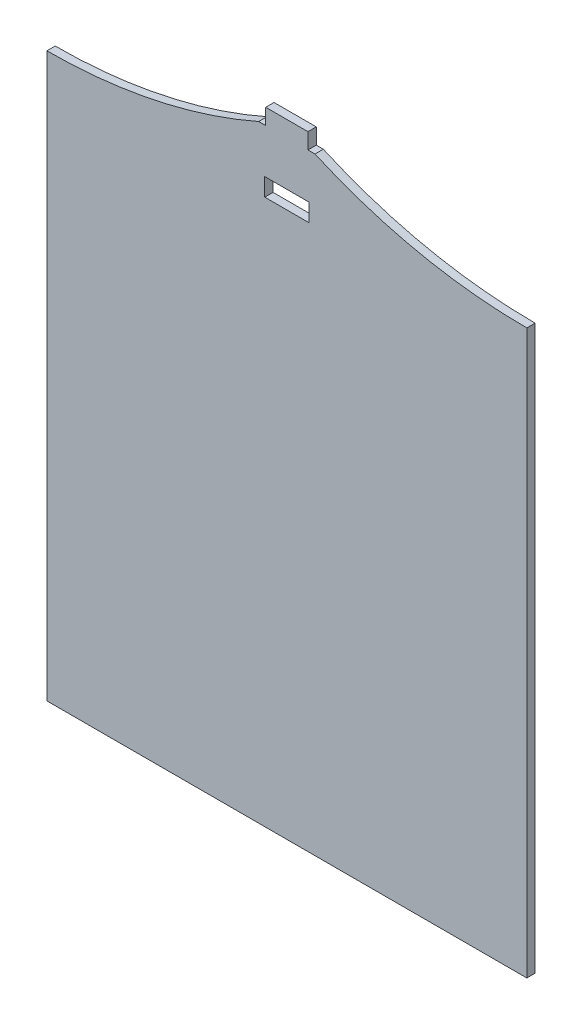
SolidWorks part; units mm, degrees
ref_plane "Front Plane" through (0, 0, 0) normal (0, 0, 1) x (1, 0, 0)
ref_plane "Top Plane" through (0, 0, 0) normal (0, 1, 0) x (1, 0, 0)
ref_plane "Right Plane" through (0, 0, 0) normal (1, 0, 0) x (0, 0, -1)
sketch "Sketch1" plane through (0, 0, 0) normal (0, 0, 1) x (1, 0, 0)
  line L0 (-56.4189, 103.1716) -> (-53.9189, 103.1716)
  line L2 (-131.6689, 87.3016) -> (-131.6689, -112.6984)
  line L3 (-131.6689, -112.6984) -> (38.8311, -112.6984)
  line L4 (38.8311, 87.3016) -> (38.8311, -112.6984)
  line L5 (-38.9189, 103.1716) -> (-36.4189, 103.1716)
  line L7 (-53.9189, 103.1716) -> (-53.9189, 108.8016)
  line L8 (-53.9189, 108.8016) -> (-38.9189, 108.8016)
  line L9 (-38.9189, 103.1716) -> (-38.9189, 108.8016)
  line L11 (-54.2689, 87.3016) -> (-38.5689, 87.3016)
  line L12 (-54.2689, 87.3016) -> (-54.2689, 80.9716)
  line L13 (-54.2689, 80.9716) -> (-38.5689, 80.9716)
  line L14 (-38.5689, 87.3016) -> (-38.5689, 80.9716)
  arc A0 (-131.6689, 87.3016) -> (-56.4189, 103.1716) centre (-131.6689, 273.6412) ccw
  arc A1 (-36.4189, 103.1716) -> (38.8311, 87.3016) centre (38.8311, 273.6412) ccw
  point P16 (0, 0)
  point P17 (-46.4189, 108.8016)
  point P18 (-46.4189, 87.3016)
  point P19 (0, 0)
  point P20 (0, 0)
  point P21 (0, 0)
  point P22 (0, 0)
  dimension "D1" = 200
  dimension "D2" = 170.5
  dimension "D4" = 20
  dimension "D3" = 15.87
  dimension "D5" = 5.63
  dimension "D6" = 15
  dimension "D7" = 15.7
  dimension "D8" = 6.33
extrude "Boss-Extrude1" add sketch "Sketch1" along normal blind 2.95
equation "\"Width\"= 170.5"
equation "\"Height\"= 200"
equation "\"thin Acrylic\"= 2.95"
equation "\"D1@Sketch1\"=\"Height\""
equation "\"D2@Sketch1\"=\"Width\""
equation "\"D1@Boss-Extrude1\"=\"thin Acrylic\""
equation "\"Thick acrylic\"= 5.63"
equation "\"Drone height\"= 21.5"
equation "\"Guard height\"= \"Drone height\" - \"Thick acrylic\""
equation "\"Support width\"= 20"
equation "\"D4@Sketch1\"=\"Support width\""
equation "\"D3@Sketch1\"=\"Guard height\""
equation "\"attach width\"= 15"
equation "\"D5@Sketch1\"=\"Thick acrylic\""
equation "\"D6@Sketch1\"=\"attach width\""
equation "\"gap\"= 0.7"
equation "\"D7@Sketch1\"=\"attach width\"+\"gap\""
equation "\"D8@Sketch1\"=\"Thick acrylic\"+\"gap\""
